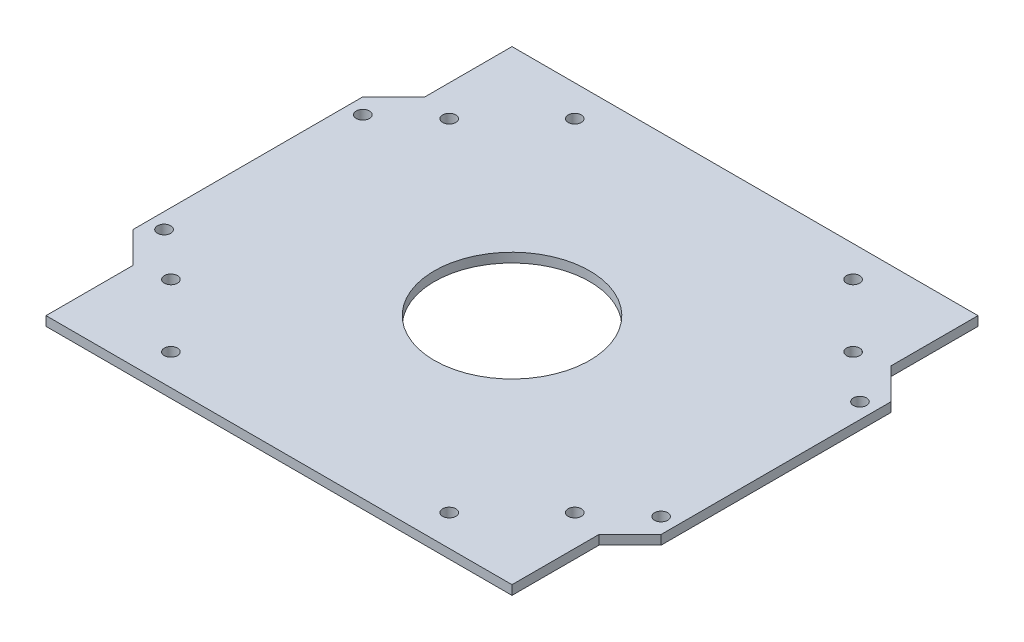
SolidWorks part; units mm, degrees
ref_plane "Front Plane" through (0, 0, 0) normal (0, 0, 1) x (1, 0, 0)
ref_plane "Top Plane" through (0, 0, 0) normal (0, 1, 0) x (1, 0, 0)
ref_plane "Right Plane" through (0, 0, 0) normal (1, 0, 0) x (0, 0, -1)
sketch "Sketch1" plane through (0, 0, 0) normal (0, 1, 0) x (1, 0, 0)
  line L1 (-75, -75) -> (75, -75)
  line L2 (-75, -75) -> (-75, 75)
  line L3 (-75, 75) -> (75, 75)
  line L4 (75, -75) -> (75, 75)
  line L5 (-75, -75) -> (75, 75) construction
  line L6 (-75, 75) -> (75, -75) construction
  point P0 (0, 0)
  dimension "D1" = 150
  dimension "D2" = 150
extrude "Boss-Extrude1" add sketch "Sketch1" along normal blind 3
sketch "Sketch2" plane through (0, 3, 0) normal (0, 1, 0) x (1, 0, 0)
  line L0 (75, 75) -> (55, 75) construction
  line L1 (-75, 75) -> (-55, 75) construction
  line L2 (-75, 75) -> (-75, 55) construction
  line L3 (-75, 55) -> (-55, 55) construction
  line L4 (-55, 75) -> (-55, 55) construction
  line L5 (75, 75) -> (75, 55) construction
  line L6 (75, 55) -> (55, 55) construction
  line L7 (55, 75) -> (55, 55) construction
  line L8 (75, -75) -> (75, -55) construction
  line L9 (75, -75) -> (55, -75) construction
  line L10 (55, -75) -> (55, -55) construction
  line L11 (75, -55) -> (55, -55) construction
  line L12 (-75, -75) -> (-55, -75) construction
  line L13 (-75, -75) -> (-75, -55) construction
  line L14 (-75, -55) -> (-55, -55) construction
  line L15 (-55, -75) -> (-55, -55) construction
  line L16 (-65, -75) -> (-65, 75) construction
  line L17 (-75, 0) -> (75, 0) construction
  line L18 (-75, 75) -> (-75, -75) construction
  line L19 (75, -75) -> (75, 75) construction
  circle A0 centre (-65, -44.8) radius 2.125
  circle A1 centre (-65, 44.8) radius 2.125
  circle A2 centre (-44.8, 65) radius 2.125
  circle A3 centre (44.8, 65) radius 2.125
  circle A4 centre (65, 44.8) radius 2.125
  circle A5 centre (65, -44.8) radius 2.125
  circle A6 centre (44.8, -65) radius 2.125
  circle A7 centre (-44.8, -65) radius 2.125
  circle A8 centre (0, 0) radius 25
  point P44 (0, 0)
  dimension "D4" = 4.25
  dimension "40" = 50
  dimension "D1" = 20
  dimension "D2" = 20
  dimension "D5" = 10.2
  dimension "D3" = 4
  dimension "D6" = 4
extrude "Cut-Extrude3" cut sketch "Sketch2" against normal through all
sketch "Sketch3" plane through (0, 3, 0) normal (0, 1, 0) x (1, 0, 0)
  line L0 (-85, 0) -> (-75, 0) construction
  line L1 (-85, -37) -> (-75, -37)
  line L2 (-85, -37) -> (-85, 37)
  line L3 (-85, 37) -> (-75, 37)
  line L5 (0, 75) -> (0, -75) construction
  line L6 (75, 75) -> (-75, 75) construction
  line L7 (-75, -75) -> (75, -75) construction
  line L8 (-75, -37) -> (-75, 37)
  line L9 (-75, 75) -> (-75, -75) construction
  line L10 (85, -37) -> (85, 37)
  line L11 (85, 37) -> (75, 37)
  line L12 (75, -37) -> (75, 37)
  line L13 (85, -37) -> (75, -37)
  circle A0 centre (-80, 32) radius 2.125
  circle A1 centre (-80, -32) radius 2.125
  circle A2 centre (80, -32) radius 2.125
  circle A3 centre (80, 32) radius 2.125
  point P0 (0, 0)
  dimension "D1" = 4.25
  dimension "D2" = 32
  dimension "D3" = 5
  dimension "D4" = 80
  dimension "D5" = 5
  dimension "D6" = 0
extrude "Boss-Extrude2" add sketch "Sketch3" against normal up to surface (3 mm away) up to face at (-65, 0, -46.925)
sketch "Sketch4" plane through (0, 3, 0) normal (0, 1, 0) x (1, 0, 0)
  line L0 (-85, 37) -> (-75, 47)
  line L1 (-75, 75) -> (-75, 37) construction
  line L2 (-75, 47) -> (-75, 37)
  line L3 (-75, 37) -> (-85, 37)
  line L4 (0, 75) -> (0, -75) construction
  line L5 (75, 75) -> (-75, 75) construction
  line L6 (-75, -75) -> (75, -75) construction
  line L7 (-85, 0) -> (85, 0) construction
  line L8 (-85, 37) -> (-85, -37) construction
  line L9 (85, -37) -> (85, 37) construction
  line L10 (75, 47) -> (75, 37)
  line L11 (85, 37) -> (75, 47)
  line L12 (75, 37) -> (85, 37)
  line L13 (85, -37) -> (75, -47)
  line L14 (75, -37) -> (85, -37)
  line L15 (75, -47) -> (75, -37)
  line L16 (-75, -47) -> (-75, -37)
  line L17 (-85, -37) -> (-75, -47)
  line L18 (-75, -37) -> (-85, -37)
  dimension "D1" = 10
extrude "Boss-Extrude3" add sketch "Sketch4" against normal up to surface (3 mm away) contours L10 L12 L11 | L3 L0 L2 | L13 L15 L14 | L16 L18 L17 up to face at (-65, 0, -46.925)
